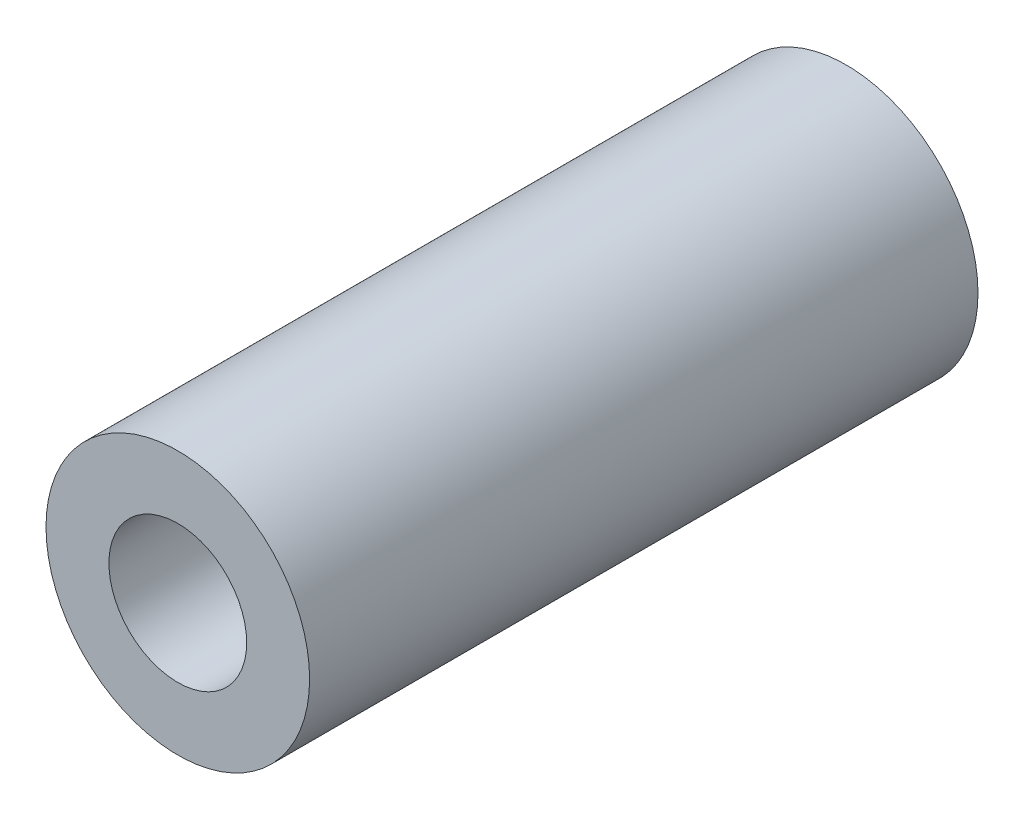
SolidWorks part; units mm, degrees
ref_plane "Front Plane" through (0, 0, 0) normal (0, 0, 1) x (1, 0, 0)
ref_plane "Top Plane" through (0, 0, 0) normal (0, 1, 0) x (1, 0, 0)
ref_plane "Right Plane" through (0, 0, 0) normal (1, 0, 0) x (0, 0, -1)
sketch "Sketch1" plane through (0, 0, 0) normal (0, 0, 1) x (1, 0, 0)
  circle A0 centre (0, 0) radius 2.4892
  circle A1 centre (0, 0) radius 4.7625
  dimension "D1" = 4.9784
  dimension "D2" = 9.525
extrude "Boss-Extrude1" add sketch "Sketch1" along normal mid plane 24.1503 contours A0 | A1
